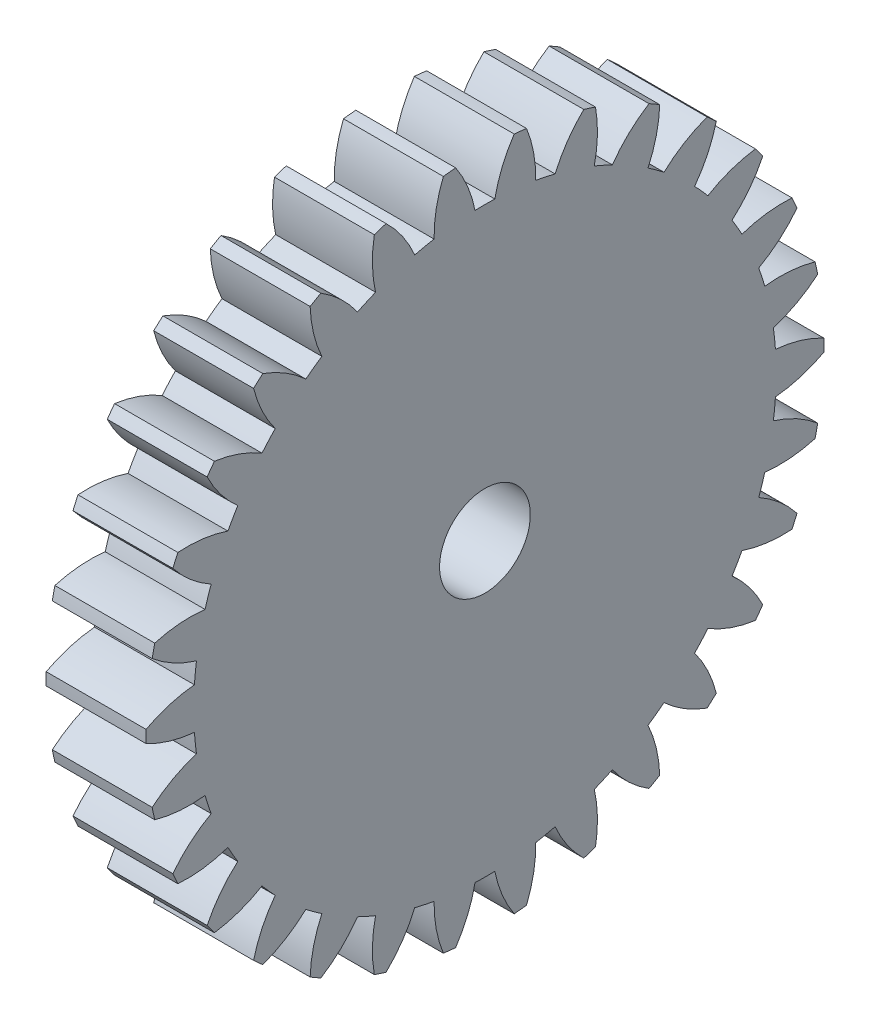
SolidWorks part; units mm, degrees
ref_plane "Plane1" through (0, 0, 0) normal (0, 0, 1) x (1, 0, 0)
ref_plane "Plane2" through (0, 0, 0) normal (0, 1, 0) x (1, 0, 0)
ref_plane "Plane3" through (0, 0, 0) normal (1, 0, 0) x (0, 0, -1)
sketch "HoldingSke" plane through (0, 0, 0) normal (0, 1, 0) x (1, 0, 0)
  line L0 (0, 0) -> (1.2372, -0.7143)
  line L1 (-15, 0) -> (100, 0) construction
  line L2 (0, 0) -> (-2.1039, 2.3779)
  line L3 (0, 0) -> (-11.863, 4.5341)
  line L4 (0, 0) -> (7.479, 4.318)
  line L5 (0, 0) -> (-46.8476, -17.4728)
  line L6 (0, 0) -> (-2.7356, -1.8457)
  line L7 (-2.1039, 2.3779) -> (8.6586, 51.2059)
  line L8 (-76.2, 54.61) -> (-75.7, 54.61)
  line L9 (-71.009, 38.7566) -> (-53.1078, 45.2721)
  line L10 (-76.2, 71.12) -> (104.1128, 71.12)
  line L11 (0, 0) -> (-3.3, 0)
  line L12 (-76.2, 101.6) -> (-76.173, 101.6)
  line L13 (24.9733, 27.94) -> (52.9518, 28.4284)
  line L14 (24.9733, 27.94) -> (24.9743, 27.94)
  line L15 (24.9733, 27.94) -> (100.4006, 29.5858)
  line L16 (-63.627, -0.7) -> (-12.827, -0.7)
  circle A0 centre (0, 0) radius 1.5
  circle A1 centre (0, 0) radius 9.624
  circle A2 centre (0, 0) radius 37.5
  circle A3 centre (0, 0) radius 1.5
  dimension "MHD" = 19.248
  dimension "Hub_dia" = 75
  dimension "Bore" = 3
  dimension "MBD" = 3
  dimension "Num_teeth" = 30
  dimension "Pitch" = 1.4286
  dimension "Overall_len" = 50
  dimension "Show_teeth" = 30
  dimension "Thickness" = 3.3
  dimension "OAL" = 50.0001
  dimension "T_dim" = 0.5
  dimension "Ap" = 20
  dimension "H" = 19.05
  dimension "Pitch_radius" = 180.3128
  dimension "Width" = 3.3
  dimension "Backlash" = 0.027
  dimension "Addendum_fac" = 1
  dimension "Dedendum_fac" = 1.25
  dimension "Clearance_fac" = 0.25
  dimension "Dedendum_add" = 0.001
  dimension "Module" = 0.7
sketch "BasProSke" plane through (0, 0, 0) normal (0, 1, 0) x (1, 0, 0)
  line L0 (-10, 0) -> (60, 0) construction
  line L1 (0, 0) -> (0, 11.2)
  line L2 (0, 0) -> (3.3, 0)
  line L3 (3.3, 0) -> (3.3, 11.2)
  line L4 (3.3, 11.2) -> (0, 11.2)
  dimension "Thickness" = 3.3
  dimension "Diameter" = 22.4
revolve "Base-Revolve" add sketch "BasProSke" angle 360 about L0
sketch "TooCutSke" plane through (0, 0, 0) normal (1, 0, 0) x (0, 0, -1)
  line L1 (0, 0) -> (0, 107) construction
  line L2 (0, 0) -> (-0.5968, 10.483) construction
  line L3 (0, 0) -> (-2.1926, 20.8611) construction
  line L4 (-0.5968, 10.483) -> (-1.0963, 10.4305) construction
  arc A0 (0.3271, 9.6184) -> (-0.3271, 9.6184) centre (0, 0) ccw
  arc A1 (0.9839, 11.1822) -> (-0.9839, 11.1822) centre (0, 0) ccw
  circle A2 centre (0, 0) radius 10.5 construction
  circle A3 centre (0, 0) radius 9.8668 construction
  arc A4 (-0.3271, 9.6184) -> (-0.9839, 11.1822) centre (-4.448, 8.8073) ccw
  arc A5 (0.9839, 11.1822) -> (0.3271, 9.6184) centre (4.448, 8.8073) ccw
  dimension "Root_dia" = 19.248
  dimension "Overcut_dia" = 22.4508
  dimension "Pitch_dia" = 21
  dimension "Base_dia" = 19.7335
  dimension "Flank_rad" = 4.2
  dimension "Half_ang" = 6
  dimension "Half_CT" = 0.5023
extrude "ToothCut" cut sketch "TooCutSke" along normal through all
fillet "Breaks" [suppressed] radius 0.014
fillet "RootFillets" [suppressed] radius 0.176
pattern_circular "TeethCuts" count 30 every 12 about axis through (-10, 0, 0) along (1, 0, 0) of "ToothCut", "RootFillets", "Breaks"
sketch "HubNeaOneSke" plane through (0, 0, 0) normal (-1, 0, 0) x (0, 0, 1)
  circle A0 centre (0, 0) radius 9.624
  dimension "Diameter" = 19.248
extrude "HubNearOne" [suppressed] add sketch "HubNeaOneSke" along normal blind 46.7001
sketch "HubNeaBotSke" plane through (0, 0, 0) normal (-1, 0, 0) x (0, 0, 1)
  circle A0 centre (0, 0) radius 9.624
  dimension "Diameter" = 19.248
extrude "HubNearBoth" [suppressed] add sketch "HubNeaBotSke" along normal blind 23.35
ref_plane "FarPln" through (3.3, 0, 0) normal (1, 0, 0) x (0, 0, -1)
sketch "HubFarSke" plane through (3.3, 0, 0) normal (1, 0, 0) x (0, 0, -1)
  circle A0 centre (0, 0) radius 9.624
  dimension "Diameter" = 19.248
extrude "HubFar" [suppressed] add sketch "HubFarSke" along normal blind 23.35
sketch "BorSke" plane through (0, 0, 0) normal (1, 0, 0) x (0, 0, -1)
  circle A0 centre (0, 0) radius 1.5
  dimension "Diameter" = 3
extrude "Bore" cut sketch "BorSke" along normal mid plane 100.0001
sketch "KeySke" plane through (0, 0, 0) normal (1, 0, 0) x (0, 0, -1)
  line L0 (-0.6, 0) -> (-0.6, 2)
  line L1 (-0.6, 2) -> (0.6, 2)
  line L2 (0.6, 2) -> (0.6, 0)
  line L3 (0, 0) -> (0, 34) construction
  line L4 (-0.6, 0) -> (0.6, 0)
  dimension "Offset" = 2
  dimension "Width" = 1.2
extrude "Keyway" [suppressed] cut sketch "KeySke" along normal mid plane 100.0001
pattern_circular "Keyway2" [suppressed] count 2 every 90 about axis through (-10, 0, 0) along (1, 0, 0)
equation "' \"Module@HoldingSke\" = 6.35"
equation "' \"Num_teeth@HoldingSke\" = 12"
equation "' \"Ap@HoldingSke\" =  20"
equation "' \"Ap@HoldingSke\" = 20"
equation "' \"Width@HoldingSke\" = 0.5 * 25.4"
equation "' \"Hub_dia@HoldingSke\"= 1 * 25.4"
equation "' \"Hub_dia@HoldingSke\" = 1 * 25.4"
equation "' \"Overall_len@HoldingSke\" = 1.0 * 25.4"
equation "' \"Bore@HoldingSke\" = 0.75 * 25.4"
equation "' \"T_dim@HoldingSke\" = 0.1 * 25.4"
equation "' \"Width@KeySke\" = 0.25 * 25.4"
equation "' \"Show_teeth@HoldingSke\" = 13"
equation "' \"Backlash@HoldingSke\" = 0.009 * 25.4"
equation "' \"Addendum_fac@HoldingSke\" = 1.0"
equation "' \"Dedendum_fac@HoldingSke\" = 1.25"
equation "' \"Dedendum_add@HoldingSke\" = 0.00005 * 25.4"
equation "' \"Clearance_fac@HoldingSke\" = 0.25"
equation "\"Pitch@HoldingSke\" = 1 / \"Module@HoldingSke\""
equation "\"Overcut_dia@TooCutSke\" = (\"Num_teeth@HoldingSke\" + 2 * \"Addendum_fac@HoldingSke\") / \"Pitch@HoldingSke\" + 0.002 * 25.4"
equation "\"Pitch_dia@TooCutSke\" = \"Num_teeth@HoldingSke\" / \"Pitch@HoldingSke\""
equation "\"Base_dia@TooCutSke\" = \"Num_teeth@HoldingSke\" / \"Pitch@HoldingSke\" * cos((\"Ap@HoldingSke\"  * 3.14159265 / 180))"
equation "\"Root_dia@TooCutSke\" = (\"Num_teeth@HoldingSke\" + 2) / \"Pitch@HoldingSke\" - 2 * (\"Addendum_fac@HoldingSke\" + \"Dedendum_fac@HoldingSke\") / \"Pitch@HoldingSke\" - \"Dedendum_add@HoldingSke\" * 2"
equation "\"Half_ang@TooCutSke\" = 180 / \"Num_teeth@HoldingSke\""
equation "\"Half_CT@TooCutSke\" = \"Num_teeth@HoldingSke\" / \"Pitch@HoldingSke\" * sin((3.14159265 / 2 / \"Num_teeth@HoldingSke\")) / 2 - 7 * \"Backlash@HoldingSke\" / 4"
equation "\"Flank_rad@TooCutSke\" = \"Num_teeth@HoldingSke\" / \"Pitch@HoldingSke\" / 5"
equation "\"Radius@RootFillets\" = \"Clearance_fac@HoldingSke\" / \"Pitch@HoldingSke\" + \"Dedendum_add@HoldingSke\""
equation "\"Break_rad@Breaks\" = 0.02 / \"Pitch@HoldingSke\""
equation "\"Thickness@HoldingSke\" = \"Width@HoldingSke\""
equation "\"OAL@HoldingSke\" = \"Thickness@HoldingSke\""
equation "\"MHD@HoldingSke\" = (\"Num_teeth@HoldingSke\" + 2) / \"Pitch@HoldingSke\" - 2 * (\"Addendum_fac@HoldingSke\" + \"Dedendum_fac@HoldingSke\")  / \"Pitch@HoldingSke\" - \"Dedendum_add@HoldingSke\" * 2"
equation "\"MBD@HoldingSke\" = (\"Num_teeth@HoldingSke\" + 2) / \"Pitch@HoldingSke\" - 2 * (\"Addendum_fac@HoldingSke\" + \"Dedendum_fac@HoldingSke\")  / \"Pitch@HoldingSke\" - \"Dedendum_add@HoldingSke\" * 2 - 0.002 * 25.4"
equation "\"MHD@HoldingSke\" = ((sgn( \"MHD@HoldingSke\" - \"Hub_dia@HoldingSke\" )-1)*( \"MHD@HoldingSke\" - \"Hub_dia@HoldingSke\" ))/-2+ \"Hub_dia@HoldingSke\""
equation "\"MBD@HoldingSke\" = ((sgn( \"MBD@HoldingSke\" - \"Bore@HoldingSke\" )-1)*( \"MBD@HoldingSke\" - \"Bore@HoldingSke\" ))/-2+ \"Bore@HoldingSke\""
equation "\"OAL@HoldingSke\" = ((sgn( \"OAL@HoldingSke\" - \"Overall_len@HoldingSke\" )+1)*( \"OAL@HoldingSke\" - \"Overall_len@HoldingSke\" ))/2 + \"Overall_len@HoldingSke\" + 0.000002 * 25.4"
equation "\"Num_teeth@TeethCuts\" = int( \"Show_teeth@HoldingSke\" ) + 1"
equation "\"Num_teeth@TeethCuts\" = ((sgn( \"Num_teeth@TeethCuts\" - \"Num_teeth@HoldingSke\" )-1)*( \"Num_teeth@TeethCuts\" - \"Num_teeth@HoldingSke\" ))/-2+ \"Num_teeth@HoldingSke\""
equation "\"Num_teeth@TeethCuts\" = ((sgn( \"Num_teeth@TeethCuts\" - 2.0)+1)*( \"Num_teeth@TeethCuts\" - 2.0))/2 +2.0"
equation "\"Angle@TeethCuts\" = 360.0 / \"Num_teeth@HoldingSke\""
equation "\"Diameter@BasProSke\" = (\"Num_teeth@HoldingSke\" + 2 * \"Addendum_fac@HoldingSke\") / \"Pitch@HoldingSke\""
equation "\"Thickness@BasProSke\"  = \"Thickness@HoldingSke\""
equation "' \"Fillet_rad@BasProSke\" =  \"Thickness@HoldingSke\" * 0.05"
equation "' \"Fillet_rad@BasProSke\" = \"Thickness@HoldingSke\" * 0.05"
equation "\"MHD@HoldingSke\" = ((sgn( \"MHD@HoldingSke\" - \"Root_dia@TooCutSke\" )-1)*( \"MHD@HoldingSke\" - \"Root_dia@TooCutSke\" ))/-2+ \"Root_dia@TooCutSke\""
equation "\"Diameter@HubNeaOneSke\" = \"MHD@HoldingSke\""
equation "\"Length@HubNearOne\" = \"OAL@HoldingSke\" - \"Thickness@BasProSke\""
equation "\"Diameter@HubNeaBotSke\" = \"MHD@HoldingSke\""
equation "\"Length@HubNearBoth\" = ( \"OAL@HoldingSke\" - \"Thickness@BasProSke\" ) / 2.0"
equation "\"Thickness@FarPln\" = \"Thickness@BasProSke\""
equation "\"Diameter@HubFarSke\" = \"MHD@HoldingSke\""
equation "\"Length@HubFar\" = ( \"OAL@HoldingSke\" - \"Thickness@BasProSke\" ) / 2.0"
equation "\"Diameter@BorSke\" = \"MBD@HoldingSke\""
equation "\"D1@Bore\" = \"OAL@HoldingSke\" * 2.0"
equation "\"D1@Keyway\" = \"OAL@HoldingSke\" * 2.0"
equation "\"Offset@KeySke\" = \"T_dim@HoldingSke\" + \"MBD@HoldingSke\" / 2.0"
